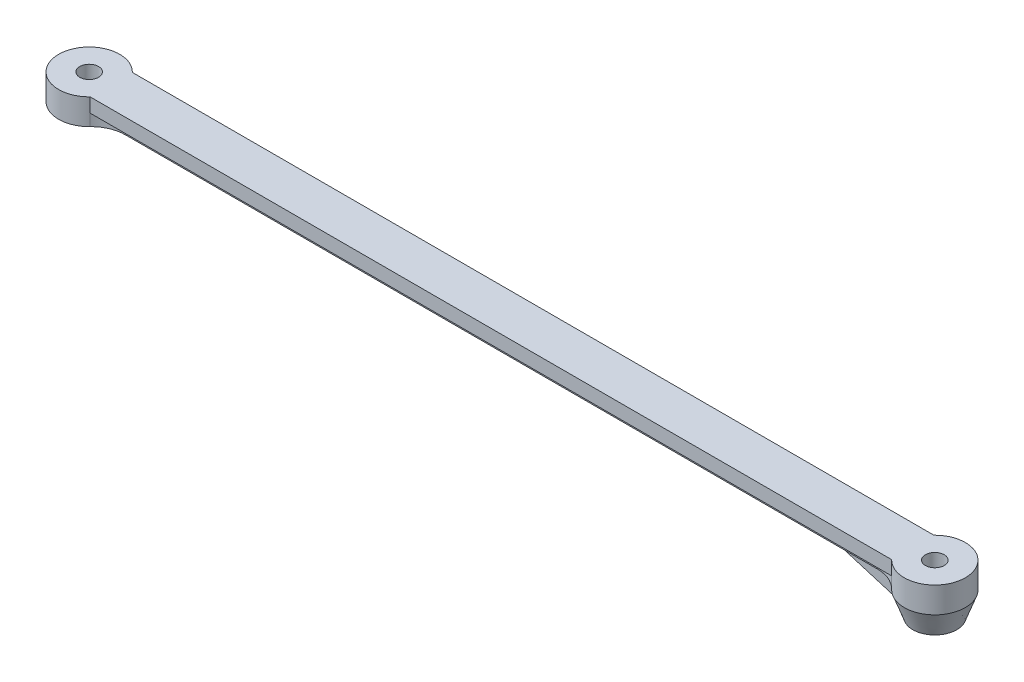
SolidWorks part; units mm, degrees
ref_plane "Front Plane" through (0, 0, 0) normal (0, 0, 1) x (1, 0, 0)
ref_plane "Top Plane" through (0, 0, 0) normal (0, 1, 0) x (1, 0, 0)
ref_plane "Right Plane" through (0, 0, 0) normal (1, 0, 0) x (0, 0, -1)
sketch "Sketch1" plane through (0, 0, 0) normal (0, 1, 0) x (1, 0, 0)
  line L0 (-180, 0) -> (-123.9881, 0) construction
  line L1 (-175.3096, 4.5) -> (-4.6904, 4.5)
  line L3 (-175.3096, -4.5) -> (-4.6904, -4.5)
  circle A0 centre (0, 0) radius 2
  circle A1 centre (-180, 0) radius 2
  arc A3 (-4.6904, -4.5) -> (-4.6904, 4.5) centre (0, 0) ccw
  arc A4 (-175.3096, 4.5) -> (-175.3096, -4.5) centre (-180, 0) ccw
  dimension "D2" = 4
  dimension "D3" = 6.5
  dimension "D1" = 180
  dimension "D4" = 9
extrude "Boss-Extrude1" add sketch "Sketch1" along normal blind 5.5
sketch "Sketch2" plane through (0, 0, 0) normal (0, -1, 0) x (1, 0, 0)
  line L0 (-6.5, 0) -> (-20.7961, 0) construction
  line L1 (-9.9671, 2.25) -> (-170.0329, 2.25)
  line L2 (-90, -4.5) -> (-90, 2.25) construction
  line L3 (-4.6904, -4.5) -> (-175.3096, -4.5) construction
  line L4 (-9.9671, -2.25) -> (-170.0329, -2.25)
  line L5 (-4.6904, 4.5) -> (-175.3096, 4.5)
  line L6 (-175.3096, -4.5) -> (-4.6904, -4.5)
  arc A0 (-4.6904, 4.5) -> (-9.9671, 2.25) centre (-9.9671, 9.5625) cw
  arc A2 (-175.3096, 4.5) -> (-170.0329, 2.25) centre (-170.0329, 9.5625) ccw
  arc A6 (-4.6904, -4.5) -> (-9.9671, -2.25) centre (-9.9671, -9.5625) ccw
  arc A7 (-4.6904, -4.5) -> (-4.6904, 4.5) centre (0, 0) ccw construction
  arc A8 (-175.3096, -4.5) -> (-170.0329, -2.25) centre (-170.0329, -9.5625) cw
  dimension "D1" = 4.5
extrude "Cut-Extrude1" cut sketch "Sketch2" against normal blind 2.5
ref_plane "Plane1" through (0, -5, 0) normal (0, -1, 0) x (-1, 0, 0)
sketch "Sketch3" plane through (0, -5, 0) normal (0, -1, 0) x (-1, 0, 0)
  circle A0 centre (0, 0) radius 4.68
  arc A1 (4.6904, 4.5) -> (4.6904, -4.5) centre (0, 0) ccw construction
  circle A2 centre (0, 0) radius 2
  circle A3 centre (0, 0) radius 2 construction
  dimension "D1" = 9.36
sketch "Sketch4" plane through (0, 0, 0) normal (0, -1, 0) x (1, 0, 0)
  circle A1 centre (0, 0) radius 6.5
  arc A2 (-4.6904, -4.5) -> (-4.6904, 4.5) centre (0, 0) ccw construction
loft "Loft1" add profiles "Sketch4" section "Sketch4" section "Sketch3"
sketch "Sketch5" plane through (0, -5, 0) normal (0, -1, 0) x (1, 0, 0)
  circle A0 centre (0, 0) radius 2
  circle A1 centre (0, 0) radius 2 construction
extrude "Cut-Extrude2" cut sketch "Sketch5" against normal through all
sketch "Sketch6" plane through (0, 0, 0) normal (0, 0, 1) x (1, 0, 0)
  line L1 (-9.9671, 0) -> (-170.0329, 0) construction
  line L4 (-170.0329, 0) -> (-9.9671, 0) construction
  line L8 (-3.08, 0) -> (-21.28, 0)
  line L11 (-21.28, 0) -> (-4.68, -5)
  line L12 (-4.68, -5) -> (-3.08, -5)
  line L13 (-3.08, -5) -> (-3.08, 0)
  line L14 (-4.68, -5) -> (4.68, -5) construction
  line L15 (-4.68, -5) -> (4.68, -5) construction
  dimension "D1" = 18.2
  dimension "D2" = 1.6
extrude "Boss-Extrude2" add sketch "Sketch6" along normal mid plane 2.5 contours L11 L12 L13 L8
equation "\"Longueur1\"= 160mm"
equation "\"Longueur2\"= 180mm"
equation "\"D1@Sketch1\"=\"Longueur2\""
